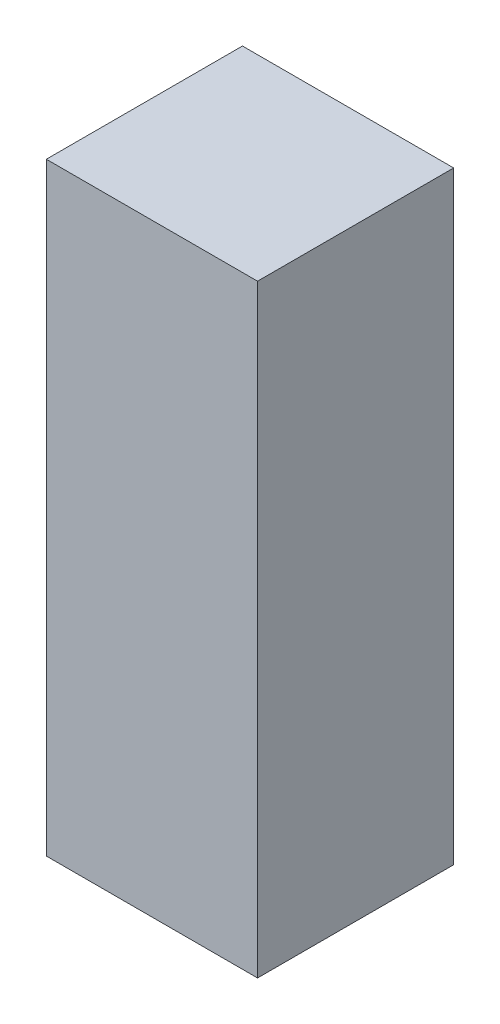
SolidWorks part; units mm, degrees
ref_plane "Front Plane" through (0, 0, 0) normal (0, 0, 1) x (1, 0, 0)
ref_plane "Top Plane" through (0, 0, 0) normal (0, 1, 0) x (1, 0, 0)
ref_plane "Right Plane" through (0, 0, 0) normal (1, 0, 0) x (0, 0, -1)
other "Configuration Table"
sketch "Sketch1" plane through (0, 0, 0) normal (0, 0, 1) x (1, 0, 0)
  line L1 (24, 220) -> (38, 220)
  line L2 (24, 220) -> (24, 260)
  line L3 (24, 260) -> (38, 260)
  line L4 (38, 220) -> (38, 260)
extrude "PACK_pano_kapagi_mentese_2_1" add sketch "Sketch1" along normal blind 13 from offset 20 separate body
